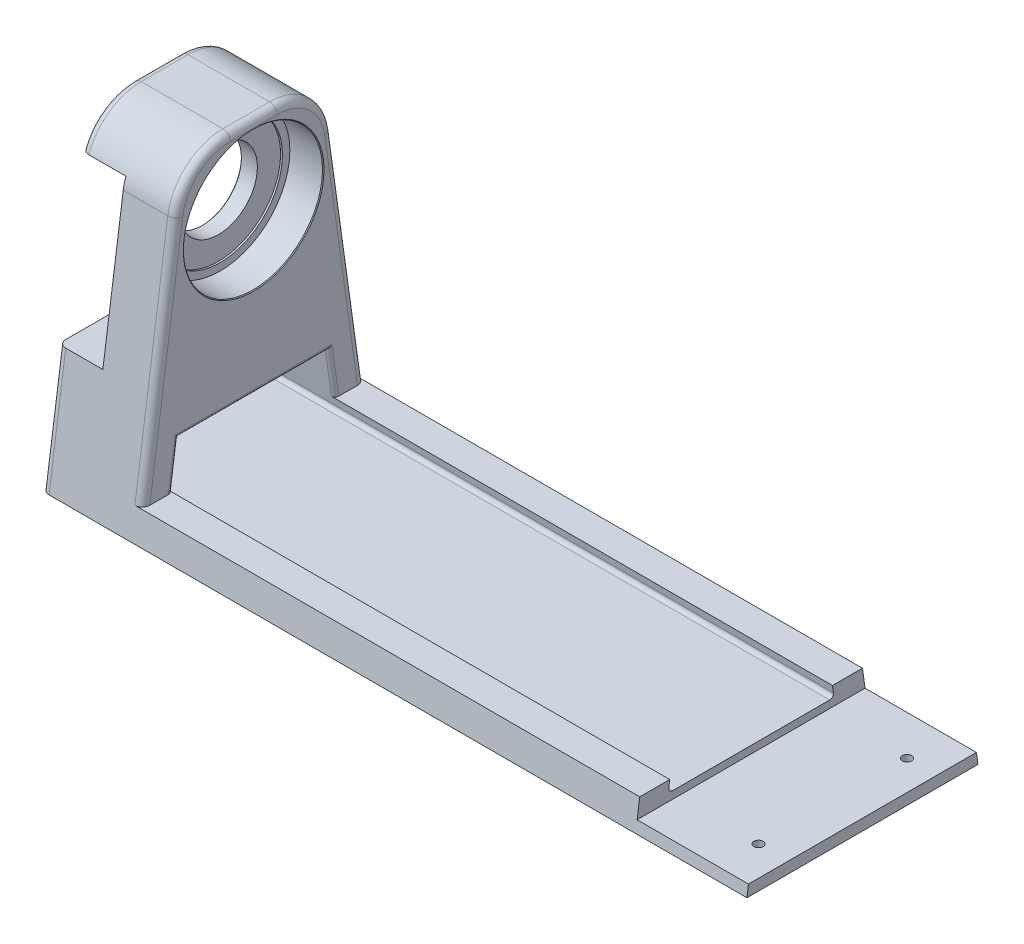
SolidWorks part; units mm, degrees
ref_plane "정면" through (0, 0, 0) normal (0, 0, 1) x (1, 0, 0)
ref_plane "윗면" through (0, 0, 0) normal (0, 1, 0) x (1, 0, 0)
ref_plane "우측면" through (0, 0, 0) normal (1, 0, 0) x (0, 0, -1)
sketch "스케치1" plane through (0, 0, 0) normal (0, 1, 0) x (1, 0, 0)
  line L1 (-95, -30) -> (95, -30)
  line L2 (-95, -30) -> (-95, 30)
  line L3 (-95, 30) -> (95, 30)
  line L4 (95, -30) -> (95, 30)
  line L5 (-95, -30) -> (95, 30) construction
  line L6 (-95, 30) -> (95, -30) construction
  point P0 (0, 0)
  dimension "D1" = 190
  dimension "D2" = 60
extrude "보스-돌출1" add sketch "스케치1" along normal blind 8
sketch "스케치2" plane through (0, 8, 0) normal (0, 1, 0) x (1, 0, 0)
  line L0 (95, 30) -> (-95, 30) construction
  line L1 (-69, -30) -> (-83, -30)
  line L2 (-69, -30) -> (-69, 30)
  line L3 (-69, 30) -> (-83, 30)
  line L4 (-83, -30) -> (-83, 30)
  line L5 (-69, -30) -> (-83, 30) construction
  line L6 (-69, 30) -> (-83, -30) construction
  line L7 (-95, 30) -> (-95, -30) construction
  point P0 (-76, 0)
  dimension "D1" = 12
  dimension "D2" = 14
extrude "보스-돌출2" add sketch "스케치2" along normal blind 76
sketch "스케치3" plane through (0, 8, 0) normal (0, 1, 0) x (1, 0, 0)
  line L1 (65, -30) -> (95, -30)
  line L2 (65, -30) -> (65, 30)
  line L3 (65, 30) -> (95, 30)
  line L4 (95, -30) -> (95, 30)
  line L5 (65, -30) -> (95, 30) construction
  line L6 (65, 30) -> (95, -30) construction
  point P0 (80, 0)
  dimension "D1" = 30
extrude "컷-돌출1" cut sketch "스케치3" against normal blind 5
draft "구배1" type of draft neutral plane draft angle 8 faces to draft 2 face at (-17.4, 20.6, -30) face at (-17.4, 20.6, 30) neutral plane through (0, 8, 0) neutral plane normal (0, 1, 0) parameters "D1"=8
sketch "스케치4" plane through (-83, 0, 0) normal (-1, 0, 0) x (0, 0, 1)
  line L0 (0, 84) -> (0, 0) construction
  line L3 (-19.3189, 84) -> (19.3189, 84) construction
  line L4 (-19.3189, 84) -> (19.3189, 84)
  line L5 (-19.3189, 84) -> (-20.7243, 74)
  line L6 (-20.7243, 74) -> (-0.75, 74)
  line L7 (19.3189, 84) -> (20.7243, 74)
  line L8 (0.75, 32) -> (26.627, 32)
  line L9 (0.75, 32) -> (0.75, 25)
  line L10 (-26.627, 32) -> (-0.75, 32)
  line L11 (-26.627, 32) -> (-30, 8)
  line L13 (26.627, 32) -> (30, 8)
  line L15 (-0.75, 32) -> (-0.75, 25)
  line L16 (-0.75, 80) -> (-0.75, 74)
  line L17 (0.75, 80) -> (0.75, 74)
  line L18 (-19.3189, 84) -> (-30, 8) construction
  line L19 (19.3189, 84) -> (30, 8) construction
  line L23 (0.75, 74) -> (20.7243, 74)
  line L24 (-0.75, 25) -> (0.75, 25)
  line L27 (-0.75, 80) -> (0.75, 80)
  line L28 (-30, 8) -> (30, 8)
  point P6 (0, 65.227)
  point P11 (0, 22.1217)
  dimension "D1" = 10
  dimension "D4" = 24
  dimension "D5" = 7
  dimension "D6" = 6
extrude "보스-돌출3" add sketch "스케치4" along normal blind 12
sketch "스케치5" plane through (-95, 0, 0) normal (-1, 0, 0) x (0, 0, 1)
  line L0 (0.75, 74) -> (20.7243, 74) construction
  line L1 (-9.25, 80) -> (9.25, 80)
  line L2 (-9.25, 80) -> (-9.25, 74)
  line L3 (-9.25, 74) -> (9.25, 74)
  line L4 (9.25, 80) -> (9.25, 74)
  line L5 (-9.25, 80) -> (9.25, 74) construction
  line L6 (-9.25, 74) -> (9.25, 80) construction
  line L8 (26.627, 32) -> (0.75, 32) construction
  line L9 (-9.25, 32) -> (9.25, 32)
  line L10 (-9.25, 32) -> (-9.25, 25)
  line L11 (-9.25, 25) -> (9.25, 25)
  line L12 (9.25, 32) -> (9.25, 25)
  line L13 (-9.25, 32) -> (9.25, 25) construction
  line L14 (-9.25, 25) -> (9.25, 32) construction
  line L15 (0, 84) -> (0, 0) construction
  line L16 (19.3189, 84) -> (-19.3189, 84) construction
  point P0 (0, 77)
  point P9 (0, 27.5)
  point P10 (0, 28.5)
  point P20 (0, 75.75)
  dimension "D1" = 18.5
  dimension "D2" = 18.5
  dimension "D3" = 6
  dimension "D4" = 7
extrude "컷-돌출2" cut sketch "스케치5" against normal blind 2.5
sketch "스케치6" plane through (-95, 0, 0) normal (-1, 0, 0) x (0, 0, 1)
  line L10 (-20.2349, 20) -> (-22.343, 5)
  line L11 (22.343, 5) -> (-22.343, 5)
  line L12 (20.2349, 20) -> (22.343, 5)
  line L13 (-26.627, 32) -> (-31.1243, 0) construction
  line L14 (26.627, 32) -> (31.1243, 0) construction
  line L15 (-31.1243, 0) -> (31.1243, 0) construction
  line L16 (-20.2349, 20) -> (20.2349, 20)
  line L17 (-9.25, 25) -> (-0.75, 25) construction
  line L18 (0, 25) -> (0, 84) construction
  line L19 (9.25, 25) -> (-9.25, 25) construction
  line L20 (-0.75, 84) -> (0.75, 84) construction
  point P22 (0, 78.5)
  point P25 (0, 61.95)
  dimension "D1" = 8
  dimension "D2" = 8
  dimension "D3" = 5
  dimension "D4" = 5
extrude "컷-돌출3" cut sketch "스케치6" against normal through all
sketch "스케치7" plane through (-69, 0, 0) normal (1, 0, 0) x (0, 0, -1)
  line L0 (0, 84) -> (0, 20) construction
  line L1 (-19.3189, 84) -> (19.3189, 84) construction
  line L2 (-20.2349, 20) -> (20.2349, 20) construction
  line L3 (30, 8) -> (21.9214, 8) construction
  circle A0 centre (0, 62.9) radius 18.75
  point P8 (0, 60.6633)
  dimension "D1" = 54.9
  dimension "D2" = 37.5
extrude "컷-돌출4" cut sketch "스케치7" against normal blind 9
sketch "스케치8" plane through (-78, 0, 0) normal (1, 0, 0) x (0, 0, -1)
  circle A0 centre (0, 62.9) radius 10.5
  dimension "D1" = 21
extrude "컷-돌출5" cut sketch "스케치8" against normal through all
sketch "스케치10" plane through (-78, 0, 0) normal (1, 0, 0) x (0, 0, -1)
  circle A0 centre (0, 62.9) radius 16.75
  circle A1 centre (0, 62.9) radius 18.75 construction
  dimension "D1" = 2
extrude "컷-돌출7" cut sketch "스케치10" against normal blind 0.5
fillet "필렛2" radius 15 2 edges at (-82, 84, -19.3189) (-82, 84, 19.3189)
fillet "필렛3" radius 1 9 edges at (-95, 12.5, 21.2889) (-95, 20, 0) (-95, 12.5, -21.2889) (-15, 5, -22.343) (-69, 14, -21.0781) (-69, 20, 0) (-69, 14, 21.0781) (-15, 5, 22.343) (-95, 5, 0)
chamfer "모따기1" distance 0.2 angle 45 2 edges at (-69, 62.9, -18.75) (-83, 62.9, -10.5)
fillet "필렛4" radius 2 10 edges at (-95, 84, 0) (-69, 84, 0) (-69, 39.5438, -25.5668) (-69, 39.5438, 25.5668) (-69, 80.3206, -16.1205) (-69, 80.3206, 16.1205) (-95, 81.2474, -14.9398) (-95, 81.2474, 14.9398) (-95, 16, 28.8757) (-95, 16, -28.8757)
sketch "스케치9" plane through (-92.5, 0, 0) normal (-1, 0, 0) x (0, 0, 1)
  line L0 (9.25, 25) -> (-9.25, 25) construction
  line L1 (-5, 76.75) -> (5, 76.75) construction
  line L2 (-5, 76.75) -> (-5, 28.15) construction
  line L3 (-5, 28.15) -> (5, 28.15) construction
  line L4 (5, 76.75) -> (5, 28.15) construction
  line L5 (-9.25, 32) -> (-9.25, 25) construction
  circle A0 centre (-5, 76.75) radius 1.25
  circle A1 centre (5, 76.75) radius 1.25
  circle A2 centre (-5, 28.15) radius 1.25
  circle A3 centre (5, 28.15) radius 1.25
  point P6 (0, 25)
  dimension "D5" = 2.5
  dimension "D1" = 48.6
  dimension "D2" = 10
  dimension "D3" = 3.15
  dimension "D4" = 4.25
extrude "컷-돌출6" cut sketch "스케치9" against normal blind 10
sketch "스케치11" plane through (0, 3, 0) normal (0, 1, 0) x (1, 0, 0)
  line L0 (87, 30.7027) -> (87, -30.7027) construction
  line L1 (95, 30.7027) -> (65, 30.7027) construction
  line L2 (65, -30.7027) -> (95, -30.7027) construction
  line L3 (95, -30.7027) -> (95, 30.7027) construction
  line L6 (65, 30) -> (-71, 30) construction
  circle A0 centre (87, 20) radius 1.25
  circle A1 centre (87, -20) radius 1.25
  dimension "D1" = 2.5
  dimension "D2" = 40
  dimension "D4" = 10
  dimension "D3" = 8
extrude "컷-돌출9" cut sketch "스케치11" against normal through all
